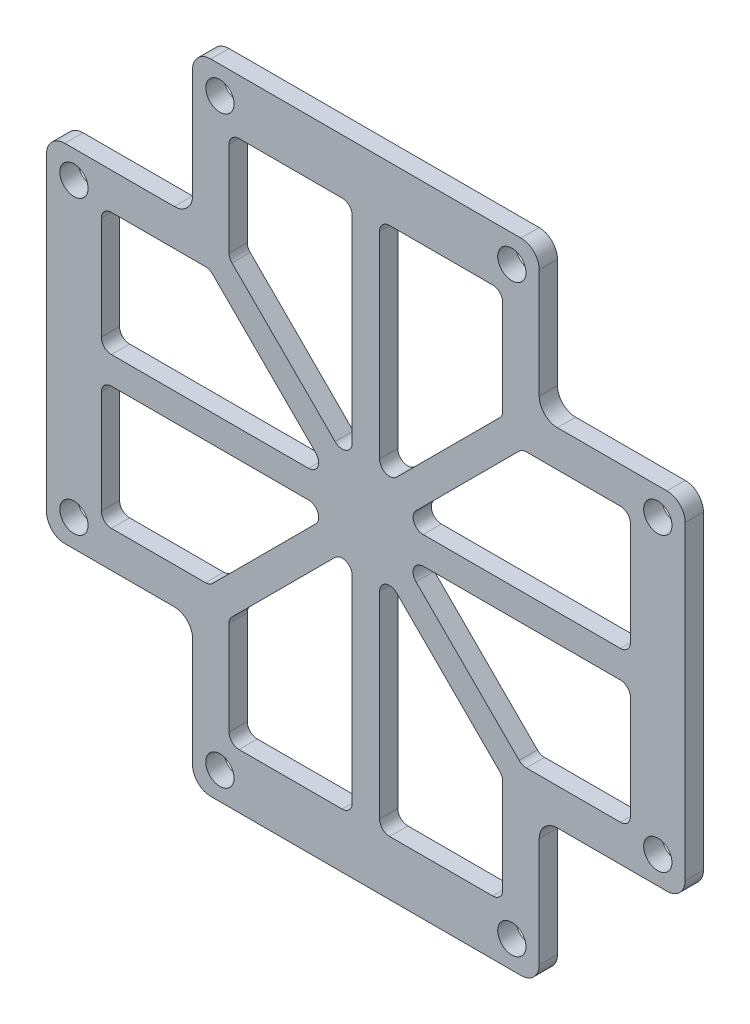
SolidWorks part; units mm, degrees
material "E-玻璃纤维"
ref_plane "前视基准面" through (0, 0, 0) normal (0, 0, 1) x (1, 0, 0)
ref_plane "上视基准面" through (0, 0, 0) normal (0, 1, 0) x (1, 0, 0)
ref_plane "右视基准面" through (0, 0, 0) normal (1, 0, 0) x (0, 0, -1)
sketch "草图1" plane through (0, 0, 0) normal (0, 0, 1) x (1, 0, 0)
  line L0 (32, 19) -> (32, -19) construction
  line L1 (-19, -35) -> (19, -35)
  line L2 (-19, -35) -> (-19, 35)
  line L3 (-19, 35) -> (19, 35)
  line L4 (19, -35) -> (19, 35)
  line L5 (0, 35) -> (0, -35) construction
  line L6 (-19, 0) -> (19, 0) construction
  line L7 (-35, -19) -> (35, -19)
  line L8 (-35, -19) -> (-35, 19)
  line L9 (-35, 19) -> (35, 19)
  line L10 (35, -19) -> (35, 19)
  line L11 (0, 19) -> (0, -19) construction
  line L12 (-35, 0) -> (35, 0) construction
  line L13 (-16, -32) -> (16, -32) construction
  line L14 (-16, -32) -> (-16, 32) construction
  line L15 (-16, 32) -> (16, 32) construction
  line L16 (16, -32) -> (16, 32) construction
  line L17 (0, 32) -> (0, -32) construction
  line L18 (-16, 0) -> (16, 0) construction
  circle A0 centre (-16, 32) radius 1.55
  circle A1 centre (16, 32) radius 1.55
  circle A2 centre (-16, -32) radius 1.55
  circle A3 centre (16, -32) radius 1.55
  circle A4 centre (32, 16) radius 1.55
  circle A5 centre (32, -16) radius 1.55
  circle A6 centre (-32, -16) radius 1.55
  circle A7 centre (-32, 16) radius 1.55
  point P0 (0, 0)
  point P4 (0, 0)
  point P8 (0, 0)
  dimension "D7" = 3.1
  dimension "D9" = 3.1
  dimension "D1" = 38
  dimension "D2" = 64
  dimension "D3" = 64
  dimension "D4" = 32
  dimension "D5" = 3
  dimension "D6" = 3
  dimension "D8" = 3
  dimension "D10" = 3
extrude "凸台-拉伸1" add sketch "草图1" along normal blind 2 contours L9 L8 L7 L2 A6 A7 | L9 L2 L7 L4 | L2 L9 L4 L3 A1 A0 | L7 L10 L9 L4 A5 A4 | L7 L2 L1 L4 A3 A2
fillet "圆角1" radius 2 12 edges at (-19, 35, 1) (19, 35, 1) (19, 19, 1) (35, 19, 1) (35, -19, 1) (19, -19, 1) (19, -35, 1) (-19, -35, 1) (-19, -19, 1) (-35, -19, 1) (-35, 19, 1) (-19, 19, 1)
sketch "草图2" plane through (0, 0, 2) normal (0, 0, 1) x (1, 0, 0)
  line L0 (-19, -33) -> (-19, -21) construction
  line L1 (-29, -15) -> (29, -15)
  line L2 (-29, -15) -> (-29, 15)
  line L3 (-29, 15) -> (29, 15)
  line L4 (29, -15) -> (29, 15)
  line L5 (0, 15) -> (0, -15) construction
  line L6 (-29, 0) -> (29, 0) construction
  line L7 (-15, -29) -> (15, -29)
  line L8 (-15, -29) -> (-15, 29)
  line L9 (-15, 29) -> (15, 29)
  line L10 (15, -29) -> (15, 29)
  line L11 (0, 29) -> (0, -29) construction
  line L12 (-15, 0) -> (15, 0) construction
  line L13 (-33, -19) -> (-21, -19) construction
  circle A0 centre (16, -32) radius 1.55 construction
  circle A1 centre (-32, -16) radius 1.55 construction
  point P0 (0, 0)
  point P4 (0, 0)
  dimension "D1" = 3
  dimension "D2" = 4
  dimension "D3" = 4
  dimension "D4" = 3
extrude "切除-拉伸1" cut sketch "草图2" against normal blind 2 contours L1 L8 L3 L2 | L10 L1 L4 L3 | L1 L10 L3 L8 | L7 L10 L1 L8 | L3 L10 L9 L8
sketch "草图3" plane through (0, 0, 2) normal (0, 0, 1) x (1, 0, 0)
  line L0 (-15, 15) -> (15, -15) construction
  line L1 (-15, -15) -> (15, 15) construction
  line L2 (0, 29) -> (0, -29) construction
  line L3 (-15, 29) -> (15, 29) construction
  line L4 (-15, -29) -> (15, -29) construction
  line L5 (-29, 0) -> (29, 0) construction
  line L6 (-29, -15) -> (-29, 15) construction
  line L7 (29, -15) -> (29, 15) construction
  line L8 (-17.1213, 15) -> (-3.6213, 1.5)
  line L9 (-15, -17.1213) -> (-1.5, -3.6213)
  line L10 (-1.5, 29) -> (-1.5, 3.6213)
  line L11 (-29, -1.5) -> (-3.6213, -1.5)
  line L12 (-15, 17.1213) -> (-1.5, 3.6213)
  line L13 (-17.1213, -15) -> (-3.6213, -1.5)
  line L14 (1.5, 29) -> (1.5, 3.6213)
  line L15 (-29, 1.5) -> (-3.6213, 1.5)
  line L16 (-13.9393, 16.0607) -> (16.0607, -13.9393) construction
  line L17 (-16.0607, 13.9393) -> (13.9393, -16.0607) construction
  line L18 (-29, 15) -> (-15, 15) construction
  line L19 (-15, 15) -> (-15, 29) construction
  line L20 (-16.0607, -13.9393) -> (13.9393, 16.0607) construction
  line L21 (15, 15) -> (15, 29) construction
  line L22 (-13.9393, -16.0607) -> (16.0607, 13.9393) construction
  line L23 (15, 15) -> (29, 15) construction
  line L24 (-29, -15) -> (-15, -15) construction
  line L25 (-15, -29) -> (-15, -15) construction
  line L26 (13.9393, -16.0607) -> (15, -17.1213)
  line L27 (15, -29) -> (15, -15) construction
  line L28 (15, -17.1213) -> (17.1213, -15)
  line L29 (15, -15) -> (29, -15) construction
  line L30 (17.1213, -15) -> (16.0607, -13.9393)
  line L31 (-17.1213, -15) -> (-15, -17.1213)
  line L32 (-1.5, -29) -> (1.5, -29)
  line L33 (-29, 1.5) -> (-29, -1.5)
  line L34 (-15, 17.1213) -> (-17.1213, 15)
  line L35 (-1.5, 29) -> (1.5, 29)
  line L36 (15, 17.1213) -> (17.1213, 15)
  line L37 (29, 1.5) -> (29, -1.5)
  line L38 (-1.5, -3.6213) -> (-1.5, -29)
  line L39 (-1.5, 29) -> (-1.5, -29) construction
  line L40 (1.5, -3.6213) -> (13.9393, -16.0607)
  line L41 (1.5, 3.6213) -> (15, 17.1213)
  line L43 (-29, -1.5) -> (29, -1.5) construction
  line L45 (3.6213, 1.5) -> (17.1213, 15)
  line L46 (-29, 1.5) -> (29, 1.5) construction
  line L47 (1.5, -3.6213) -> (1.5, -29)
  line L48 (3.6213, 1.5) -> (29, 1.5)
  line L49 (3.6213, -1.5) -> (16.0607, -13.9393)
  line L50 (1.5, 29) -> (1.5, -29) construction
  line L51 (3.6213, -1.5) -> (29, -1.5)
  dimension "D1" = 1.5
  dimension "D2" = 1.5
extrude "凸台-拉伸2" add sketch "草图3" against normal up to surface (2 mm away) up to face at (0, 0, 0)
fillet "圆角2" radius 1.1 32 edges at (15, -29, 1) (1.5, -29, 1) (1.5, -3.6213, 1) (15, -17.1213, 1) (29, 15, 1) (29, 1.5, 1) (3.6213, 1.5, 1) (17.1213, 15, 1) (-15, 29, 1) (-1.5, 29, 1) (-1.5, 3.6213, 1) (-15, 17.1213, 1) (-29, -15, 1) (-29, -1.5, 1) (-3.6213, -1.5, 1) (-17.1213, -15, 1) (-1.5, -3.6213, 1) (-1.5, -29, 1) (-15, -29, 1) (-15, -17.1213, 1) (3.6213, -1.5, 1) (29, -1.5, 1) (29, -15, 1) (17.1213, -15, 1) (1.5, 3.6213, 1) (1.5, 29, 1) (15, 29, 1) (15, 17.1213, 1) (-29, 15, 1) (-17.1213, 15, 1) (-29, 1.5, 1) (-3.6213, 1.5, 1)
